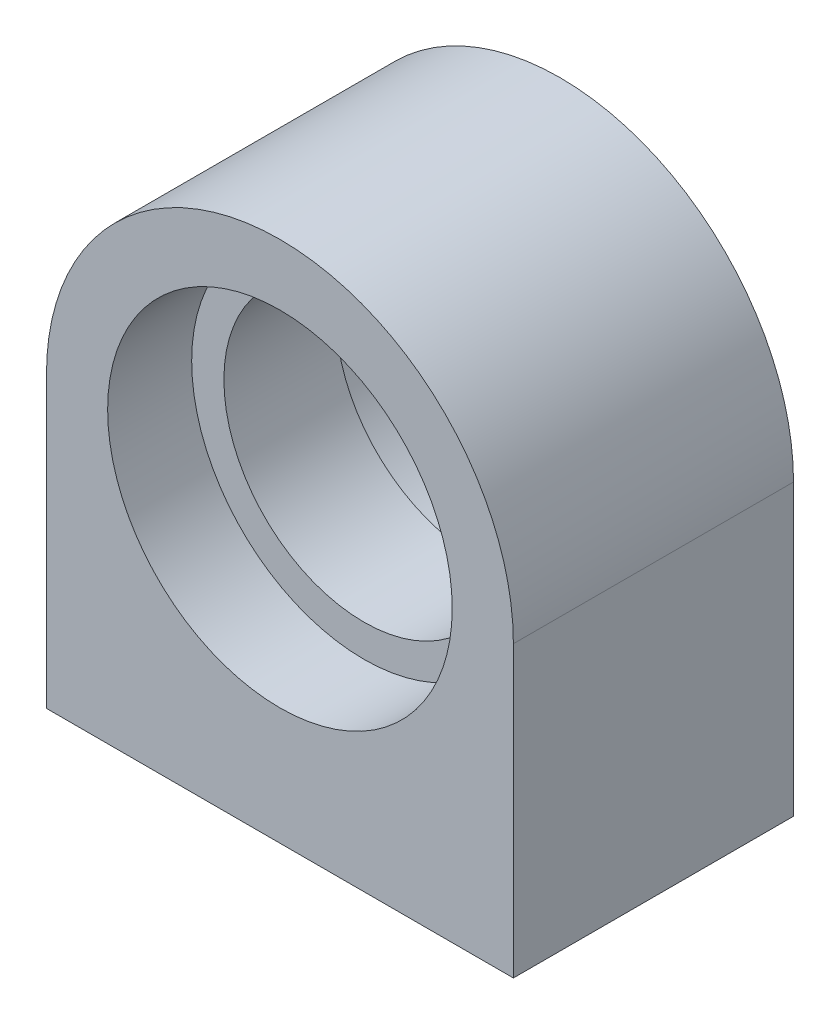
SolidWorks part; units mm, degrees
ref_plane "Ebene vorne" through (0, 0, 0) normal (0, 0, 1) x (1, 0, 0)
ref_plane "Ebene oben" through (0, 0, 0) normal (0, 1, 0) x (1, 0, 0)
ref_plane "Ebene rechts" through (0, 0, 0) normal (1, 0, 0) x (0, 0, -1)
sketch "Skizze1" plane through (0, 0, 0) normal (0, 0, 1) x (1, 0, 0)
  line L0 (0, 40.5) -> (0.8271, 40.5) construction
  line L1 (-25, -15.5) -> (25, -15.5)
  line L2 (-25, -15.5) -> (-25, 15.5)
  line L3 (-25, 15.5) -> (25, 15.5)
  line L4 (25, -15.5) -> (25, 15.5)
  line L5 (-25, -15.5) -> (25, 15.5) construction
  line L6 (-25, 15.5) -> (25, -15.5) construction
  circle A0 centre (0, 15.5) radius 25
  circle A1 centre (0, 15.5) radius 15
  point P0 (0, 0)
  dimension "D1" = 56
  dimension "D2" = 50
extrude "Aufsatz-Linear austragen1" add sketch "Skizze1" along normal mid plane 30 contours A1 L3 A0 | A1 L3 A0 | A0 L2 L1 L4
sketch "Skizze3" plane through (0, 0, 15) normal (0, 0, 1) x (1, 0, 0)
  circle A0 centre (0, 15.5) radius 18.45
  dimension "D1" = 36.9
extrude "Schnitt-Linear austragen1" cut sketch "Skizze3" against normal blind 9
mirror "Spiegeln1" about plane through (0, 0, 0) normal (0, 0, 1) of "Schnitt-Linear austragen1"
sketch "Skizze4" plane through (0, -15.5, 0) normal (0, -1, 0) x (1, 0, 0)
  line L0 (-25, 0) -> (25, 0) construction
  line L1 (-25, 15) -> (-25, -15) construction
  line L2 (25, 15) -> (25, -15) construction
  line L3 (-25, 0) -> (-17, 0) construction
  line L4 (0, 0) -> (0, 6.6092) construction
  circle A0 centre (-17, 0) radius 1.65
  circle A1 centre (-7, 0) radius 1.65
  circle A2 centre (7, 0) radius 1.65
  circle A3 centre (17, 0) radius 1.65
  dimension "D3" = 3.3
  dimension "D4" = 3.3
  dimension "D1" = 8
  dimension "D2" = 10
extrude "Schnitt-Linear austragen2" cut sketch "Skizze4" against normal blind 11
